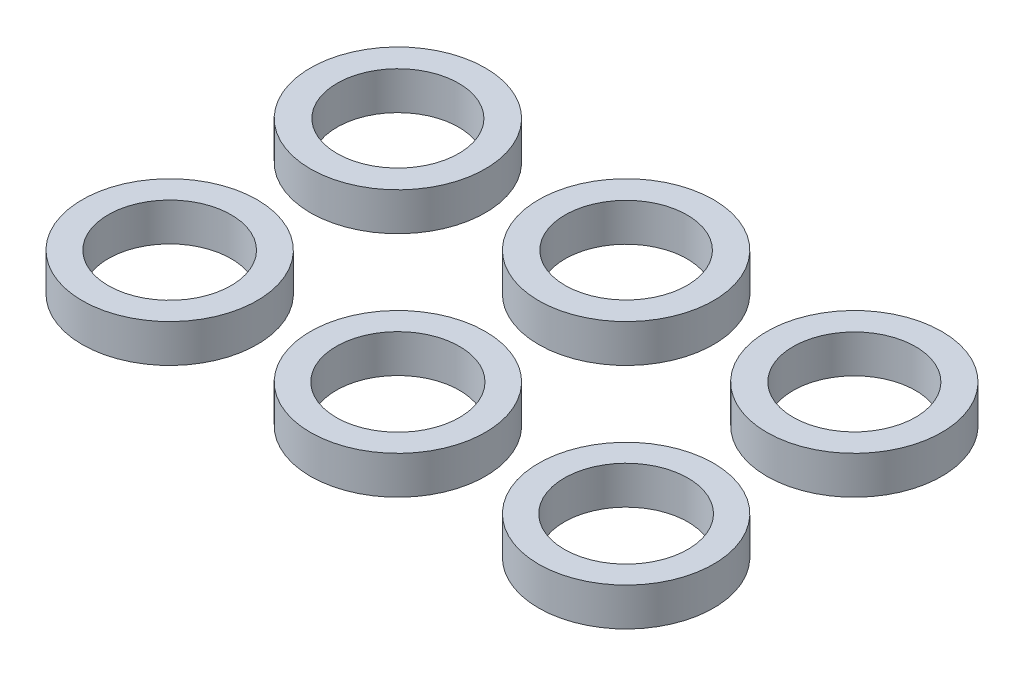
SolidWorks part; units mm, degrees
ref_plane "Front Plane" through (0, 0, 0) normal (0, 0, 1) x (1, 0, 0)
ref_plane "Top Plane" through (0, 0, 0) normal (0, 1, 0) x (1, 0, 0)
ref_plane "Right Plane" through (0, 0, 0) normal (1, 0, 0) x (0, 0, -1)
sketch "Sketch1" plane through (0, 0, 0) normal (0, 1, 0) x (1, 0, 0)
  circle A0 centre (0, 0) radius 11.5
  circle A1 centre (0, 0) radius 8
  circle A2 centre (30, 0) radius 11.5
  circle A3 centre (60, 0) radius 11.5
  circle A4 centre (30, -30) radius 11.5
  circle A5 centre (60, -30) radius 11.5
  circle A6 centre (0, -30) radius 11.5
  circle A7 centre (30, 0) radius 8.025
  circle A8 centre (60, 0) radius 8.05
  circle A9 centre (0, -30) radius 8.075
  circle A10 centre (30, -30) radius 8.1
  circle A11 centre (60, -30) radius 8.125
  dimension "D1" = 16
  dimension "D2" = 23
  dimension "D5" = 16.05
  dimension "D6" = 16.1
  dimension "D7" = 16.15
  dimension "D8" = 16.2
  dimension "D9" = 16.25
  dimension "D3" = 3
  dimension "D4" = 2
extrude "Boss-Extrude1" add sketch "Sketch1" along normal blind 5
